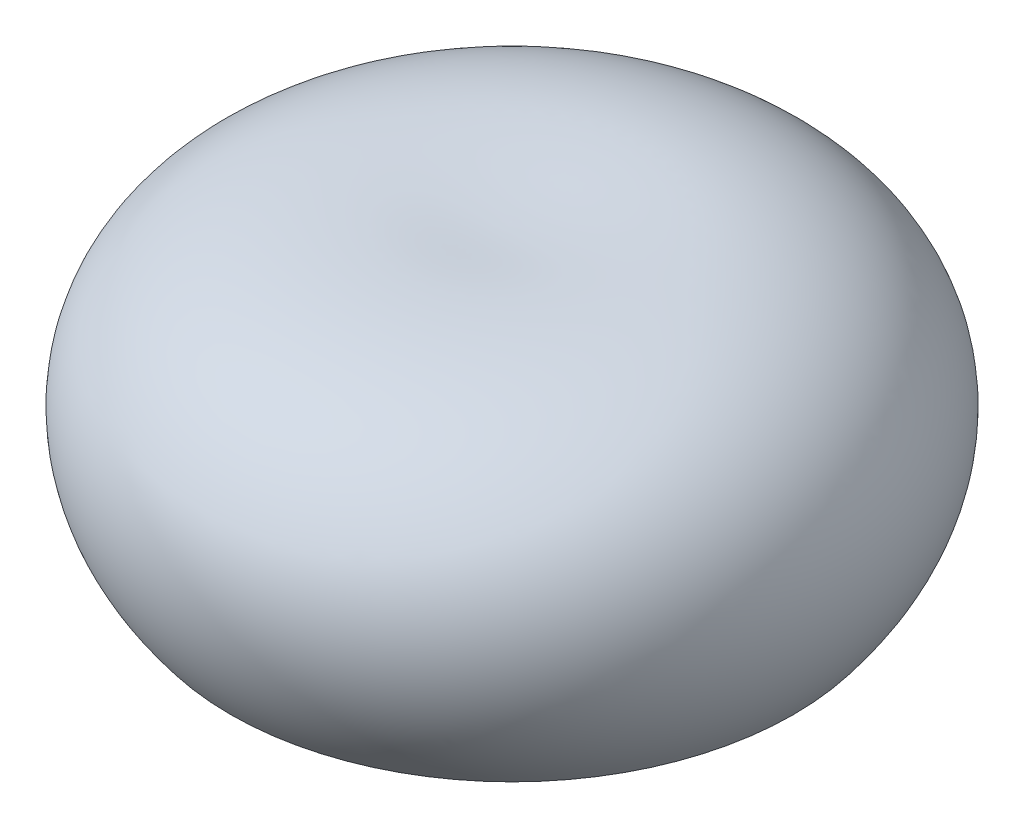
SolidWorks part; units mm, degrees
ref_plane "前视基准面" through (0, 0, 0) normal (0, 0, 1) x (1, 0, 0)
ref_plane "上视基准面" through (0, 0, 0) normal (0, 1, 0) x (1, 0, 0)
ref_plane "右视基准面" through (0, 0, 0) normal (1, 0, 0) x (0, 0, -1)
curve "曲线1"
  spline degree 3 poles (0, 7, 0) (0.0738, 6.9995, 0) (0.1783, 6.9989, 0) (0.3064, 7.0015, 0) (0.3805, 7.0034, 0) (0.4416, 7.0054, 0) (0.4951, 7.0074, 0) (0.5433, 7.0093, 0) (0.5877, 7.0113, 0) (0.629, 7.0132, 0) (0.6679, 7.0151, 0) (0.7047, 7.017, 0) (0.7397, 7.0189, 0) (0.7733, 7.0208, 0) (0.8056, 7.0227, 0) (0.8367, 7.0245, 0) (0.8668, 7.0264, 0) (0.8959, 7.0282, 0) (0.9242, 7.03, 0) (0.9518, 7.0318, 0) (0.9786, 7.0335, 0) (1.0048, 7.0353, 0) (1.0305, 7.037, 0) (1.0555, 7.0387, 0) (1.0801, 7.0405, 0) (1.1041, 7.0421, 0) (1.1278, 7.0438, 0) (1.151, 7.0455, 0) (1.1738, 7.0471, 0) (1.1962, 7.0487, 0) (1.2183, 7.0503, 0) (1.2401, 7.0519, 0) (1.2615, 7.0535, 0) (1.2826, 7.055, 0) (1.3035, 7.0566, 0) (1.3241, 7.0581, 0) (1.3444, 7.0596, 0) (1.3645, 7.0611, 0) (1.3843, 7.0626, 0) (1.4039, 7.064, 0) (1.4233, 7.0654, 0) (1.4425, 7.0669, 0) (1.4614, 7.0683, 0) (1.4802, 7.0697, 0) (1.4988, 7.071, 0) (1.5172, 7.0724, 0) (1.5355, 7.0737, 0) (1.5535, 7.0751, 0) (1.5714, 7.0764, 0) (1.5892, 7.0777, 0) (1.6068, 7.0789, 0) (1.6243, 7.0802, 0) (1.6416, 7.0815, 0) (1.6588, 7.0827, 0) (1.6758, 7.0839, 0) (1.6927, 7.0851, 0) (1.7095, 7.0863, 0) (1.7262, 7.0875, 0) (1.7427, 7.0886, 0) (1.7592, 7.0897, 0) (1.7755, 7.0909, 0) (1.7917, 7.092, 0) (1.8078, 7.0931, 0) (1.8238, 7.0941, 0) (1.8397, 7.0952, 0) (1.8555, 7.0962, 0) (1.8713, 7.0973, 0) (1.8869, 7.0983, 0) (1.9024, 7.0993, 0) (1.9178, 7.1003, 0) (1.9332, 7.1012, 0) (1.9485, 7.1022, 0) (1.9636, 7.1031, 0) (1.9788, 7.104, 0) (1.9938, 7.1049, 0) (2.0087, 7.1058, 0) (2.0236, 7.1067, 0) (2.0384, 7.1076, 0) (2.0531, 7.1084, 0) (2.0678, 7.1092, 0) (2.0823, 7.1101, 0) (2.0969, 7.1109, 0) (2.1113, 7.1116, 0) (2.1257, 7.1124, 0) (2.14, 7.1132, 0) (2.1543, 7.1139, 0) (2.1684, 7.1147, 0) (2.1826, 7.1154, 0) (2.1966, 7.1161, 0) (2.2107, 7.1167, 0) (2.2246, 7.1174, 0) (2.2385, 7.1181, 0) (2.2524, 7.1187, 0) (2.2661, 7.1193, 0) (2.2799, 7.1199, 0) (2.2936, 7.1205, 0) (2.3072, 7.1211, 0) (2.3208, 7.1217, 0) (2.3343, 7.1222, 0) (2.3478, 7.1228, 0) (2.3612, 7.1233, 0) (2.3746, 7.1238, 0) (2.3879, 7.1243, 0) (2.4012, 7.1248, 0) (2.4145, 7.1253, 0) (2.4277, 7.1257, 0) (2.4408, 7.1262, 0) (2.4539, 7.1266, 0) (2.467, 7.127, 0) (2.48, 7.1274, 0) (2.493, 7.1278, 0) (2.506, 7.1281, 0) (2.5189, 7.1285, 0) (2.5317, 7.1288, 0) (2.5446, 7.1292, 0) (2.5574, 7.1295, 0) (2.5701, 7.1298, 0) (2.5828, 7.1301, 0) (2.5955, 7.1303, 0) (2.6081, 7.1306, 0) (2.6207, 7.1308, 0) (2.6333, 7.1311, 0) (2.6458, 7.1313, 0) (2.6583, 7.1315, 0) (2.6708, 7.1317, 0) (2.6832, 7.1318, 0) (2.6956, 7.132, 0) (2.708, 7.1321, 0) (2.7203, 7.1323, 0) (2.7326, 7.1324, 0) (2.7449, 7.1325, 0) (2.7571, 7.1326, 0) (2.7693, 7.1327, 0) (2.7815, 7.1327, 0) (2.7937, 7.1328, 0) (2.8058, 7.1328, 0) (2.8179, 7.1328, 0) (2.8299, 7.1329, 0) (2.8419, 7.1328, 0) (2.8539, 7.1328, 0) (2.8659, 7.1328, 0) (2.8779, 7.1328, 0) (2.8898, 7.1327, 0) (2.9017, 7.1326, 0) (2.9135, 7.1325, 0) (2.9254, 7.1324, 0) (2.9372, 7.1323, 0) (2.949, 7.1322, 0) (2.9607, 7.1321, 0) (2.9725, 7.1319, 0) (2.9842, 7.1317, 0) (2.9958, 7.1316, 0) (3.0075, 7.1314, 0) (3.0191, 7.1312, 0) (3.0307, 7.1309, 0) (3.0423, 7.1307, 0) (3.0539, 7.1305, 0) (3.0654, 7.1302, 0) (3.0769, 7.1299, 0) (3.0884, 7.1296, 0) (3.0999, 7.1293, 0) (3.1114, 7.129, 0) (3.1228, 7.1287, 0) (3.1342, 7.1284, 0) (3.1456, 7.128, 0) (3.1569, 7.1277, 0) (3.1683, 7.1273, 0) (3.1796, 7.1269, 0) (3.1909, 7.1265, 0) (3.2021, 7.1261, 0) (3.2134, 7.1256, 0) (3.2246, 7.1252, 0) (3.2358, 7.1247, 0) (3.247, 7.1243, 0) (3.2582, 7.1238, 0) (3.2694, 7.1233, 0) (3.2805, 7.1228, 0) (3.2916, 7.1222, 0) (3.3027, 7.1217, 0) (3.3138, 7.1211, 0) (3.3248, 7.1206, 0) (3.3359, 7.12, 0) (3.3469, 7.1194, 0) (3.3579, 7.1188, 0) (3.3689, 7.1182, 0) (3.3798, 7.1176, 0) (3.3908, 7.1169, 0) (3.4017, 7.1163, 0) (3.4126, 7.1156, 0) (3.4235, 7.1149, 0) (3.4344, 7.1142, 0) (3.4452, 7.1135, 0) (3.4561, 7.1128, 0) (3.4669, 7.1121, 0) (3.4777, 7.1113, 0) (3.4885, 7.1106, 0) (3.4993, 7.1098, 0) (3.51, 7.109, 0) (3.5208, 7.1082, 0) (3.5315, 7.1074, 0) (3.5422, 7.1066, 0) (3.5529, 7.1058, 0) (3.5635, 7.1049, 0) (3.5742, 7.104, 0) (3.5848, 7.1032, 0) (3.5955, 7.1023, 0) (3.6061, 7.1014, 0) (3.6167, 7.1005, 0) (3.6273, 7.0995, 0) (3.6378, 7.0986, 0) (3.6484, 7.0977, 0) (3.6589, 7.0967, 0) (3.6694, 7.0957, 0) (3.6799, 7.0947, 0) (3.6904, 7.0937, 0) (3.7009, 7.0927, 0) (3.7114, 7.0917, 0) (3.7218, 7.0906, 0) (3.7322, 7.0896, 0) (3.7426, 7.0885, 0) (3.753, 7.0874, 0) (3.7634, 7.0863, 0) (3.7738, 7.0852, 0) (3.7842, 7.0841, 0) (3.7945, 7.083, 0) (3.8049, 7.0818, 0) (3.8152, 7.0807, 0) (3.8255, 7.0795, 0) (3.8358, 7.0783, 0) (3.846, 7.0771, 0) (3.8563, 7.0759, 0) (3.8666, 7.0747, 0) (3.8768, 7.0734, 0) (3.887, 7.0722, 0) (3.8972, 7.0709, 0) (3.9074, 7.0697, 0) (3.9176, 7.0684, 0) (3.9278, 7.0671, 0) (3.938, 7.0658, 0) (3.9481, 7.0644, 0) (3.9582, 7.0631, 0) (3.9684, 7.0618, 0) (3.9785, 7.0604, 0) (3.9886, 7.059, 0) (3.9986, 7.0576, 0) (4.0087, 7.0562, 0) (4.0188, 7.0548, 0) (4.0288, 7.0534, 0) (4.0389, 7.0519, 0) (4.0489, 7.0505, 0) (4.0589, 7.049, 0) (4.0689, 7.0475, 0) (4.0789, 7.0461, 0) (4.0889, 7.0445, 0) (4.0988, 7.043, 0) (4.1088, 7.0415, 0) (4.1187, 7.04, 0) (4.1286, 7.0384, 0) (4.1386, 7.0368, 0) (4.1485, 7.0352, 0) (4.1584, 7.0337, 0) (4.1682, 7.032, 0) (4.1781, 7.0304, 0) (4.188, 7.0288, 0) (4.1978, 7.0271, 0) (4.2076, 7.0255, 0) (4.2175, 7.0238, 0) (4.2273, 7.0221, 0) (4.2371, 7.0204, 0) (4.2469, 7.0187, 0) (4.2567, 7.017, 0) (4.2664, 7.0153, 0) (4.2762, 7.0135, 0) (4.2859, 7.0118, 0) (4.2957, 7.01, 0) (4.3054, 7.0082, 0) (4.3151, 7.0064, 0) (4.3248, 7.0046, 0) (4.3345, 7.0028, 0) (4.3442, 7.0009, 0) (4.3539, 6.9991, 0) (4.3635, 6.9972, 0) (4.3732, 6.9953, 0) (4.3828, 6.9934, 0) (4.3924, 6.9915, 0) (4.4021, 6.9896, 0) (4.4117, 6.9877, 0) (4.4213, 6.9858, 0) (4.4309, 6.9838, 0) (4.4404, 6.9818, 0) (4.45, 6.9799, 0) (4.4596, 6.9779, 0) (4.4691, 6.9759, 0) (4.4786, 6.9738, 0) (4.4882, 6.9718, 0) (4.4977, 6.9698, 0) (4.5072, 6.9677, 0) (4.5167, 6.9656, 0) (4.5262, 6.9635, 0) (4.5356, 6.9615, 0) (4.5451, 6.9593, 0) (4.5546, 6.9572, 0) (4.564, 6.9551, 0) (4.5734, 6.9529, 0) (4.5829, 6.9508, 0) (4.5923, 6.9486, 0) (4.6017, 6.9464, 0) (4.6111, 6.9442, 0) (4.6205, 6.942, 0) (4.6299, 6.9398, 0) (4.6392, 6.9375, 0) (4.6486, 6.9353, 0) (4.6579, 6.933, 0) (4.6673, 6.9307, 0) (4.6766, 6.9284, 0) (4.6859, 6.9261, 0) (4.6952, 6.9238, 0) (4.7045, 6.9215, 0) (4.7138, 6.9192, 0) (4.7231, 6.9168, 0) (4.7324, 6.9144, 0) (4.7416, 6.912, 0) (4.7509, 6.9096, 0) (4.7601, 6.9072, 0) (4.7693, 6.9048, 0) (4.7786, 6.9024, 0) (4.7878, 6.8999, 0) (4.797, 6.8975, 0) (4.8062, 6.895, 0) (4.8154, 6.8925, 0) (4.8245, 6.89, 0) (4.8337, 6.8875, 0) (4.8429, 6.885, 0) (4.852, 6.8824, 0) (4.8612, 6.8799, 0) (4.8703, 6.8773, 0) (4.8794, 6.8747, 0) (4.8885, 6.8721, 0) (4.8976, 6.8695, 0) (4.9067, 6.8669, 0) (4.9158, 6.8643, 0) (4.9249, 6.8616, 0) (4.9339, 6.859, 0) (4.943, 6.8563, 0) (4.952, 6.8536, 0) (4.9611, 6.8509, 0) (4.9701, 6.8482, 0) (4.9791, 6.8455, 0) (4.9881, 6.8428, 0) (4.9971, 6.84, 0) (5.0061, 6.8372, 0) (5.0151, 6.8345, 0) (5.0241, 6.8317, 0) (5.0331, 6.8289, 0) (5.042, 6.8261, 0) (5.051, 6.8232, 0) (5.0599, 6.8204, 0) (5.0688, 6.8175, 0) (5.0778, 6.8147, 0) (5.0867, 6.8118, 0) (5.0956, 6.8089, 0) (5.1045, 6.806, 0) (5.1134, 6.803, 0) (5.1222, 6.8001, 0) (5.1311, 6.7971, 0) (5.14, 6.7942, 0) (5.1488, 6.7912, 0) (5.1576, 6.7882, 0) (5.1665, 6.7852, 0) (5.1753, 6.7822, 0) (5.1841, 6.7792, 0) (5.1929, 6.7761, 0) (5.2017, 6.7731, 0) (5.2105, 6.77, 0) (5.2193, 6.7669, 0) (5.228, 6.7638, 0) (5.2368, 6.7607, 0) (5.2456, 6.7576, 0) (5.2543, 6.7544, 0) (5.263, 6.7513, 0) (5.2718, 6.7481, 0) (5.2805, 6.7449, 0) (5.2892, 6.7417, 0) (5.2979, 6.7385, 0) (5.3066, 6.7353, 0) (5.3153, 6.7321, 0) (5.3239, 6.7288, 0) (5.3326, 6.7256, 0) (5.3412, 6.7223, 0) (5.3499, 6.719, 0) (5.3585, 6.7157, 0) (5.3671, 6.7124, 0) (5.3758, 6.709, 0) (5.3844, 6.7057, 0) (5.393, 6.7023, 0) (5.4016, 6.699, 0) (5.4102, 6.6956, 0) (5.4187, 6.6922, 0) (5.4273, 6.6888, 0) (5.4359, 6.6854, 0) (5.4444, 6.6819, 0) (5.4529, 6.6785, 0) (5.4615, 6.675, 0) (5.47, 6.6715, 0) (5.4785, 6.668, 0) (5.487, 6.6645, 0) (5.4955, 6.661, 0) (5.504, 6.6575, 0) (5.5125, 6.6539, 0) (5.5209, 6.6503, 0) (5.5294, 6.6468, 0) (5.5378, 6.6432, 0) (5.5463, 6.6396, 0) (5.5547, 6.6359, 0) (5.5631, 6.6323, 0) (5.5716, 6.6287, 0) (5.58, 6.625, 0) (5.5884, 6.6213, 0) (5.5968, 6.6176, 0) (5.6051, 6.6139, 0) (5.6135, 6.6102, 0) (5.6219, 6.6065, 0) (5.6302, 6.6027, 0) (5.6386, 6.599, 0) (5.6469, 6.5952, 0) (5.6552, 6.5914, 0) (5.6635, 6.5876, 0) (5.6719, 6.5838, 0) (5.6802, 6.58, 0) (5.6884, 6.5761, 0) (5.6967, 6.5723, 0) (5.705, 6.5684, 0) (5.7133, 6.5645, 0) (5.7215, 6.5606, 0) (5.7298, 6.5567, 0) (5.738, 6.5528, 0) (5.7462, 6.5488, 0) (5.7544, 6.5449, 0) (5.7627, 6.5409, 0) (5.7709, 6.5369, 0) (5.7791, 6.5329, 0) (5.7872, 6.5289, 0) (5.7954, 6.5249, 0) (5.8036, 6.5208, 0) (5.8117, 6.5168, 0) (5.8199, 6.5127, 0) (5.828, 6.5086, 0) (5.8361, 6.5045, 0) (5.8443, 6.5004, 0) (5.8524, 6.4962, 0) (5.8605, 6.4921, 0) (5.8686, 6.4879, 0) (5.8766, 6.4838, 0) (5.8847, 6.4796, 0) (5.8928, 6.4754, 0) (5.9008, 6.4712, 0) (5.9089, 6.4669, 0) (5.9169, 6.4627, 0) (5.9249, 6.4584, 0) (5.933, 6.4541, 0) (5.941, 6.4499, 0) (5.949, 6.4456, 0) (5.957, 6.4412, 0) (5.9649, 6.4369, 0) (5.9729, 6.4326, 0) (5.9809, 6.4282, 0) (5.9888, 6.4238, 0) (5.9968, 6.4194, 0) (6.0047, 6.415, 0) (6.0126, 6.4106, 0) (6.0206, 6.4062, 0) (6.0285, 6.4017, 0) (6.0364, 6.3972, 0) (6.0442, 6.3928, 0) (6.0521, 6.3883, 0) (6.06, 6.3838, 0) (6.0679, 6.3792, 0) (6.0757, 6.3747, 0) (6.0835, 6.3701, 0) (6.0914, 6.3656, 0) (6.0992, 6.361, 0) (6.107, 6.3564, 0) (6.1148, 6.3518, 0) (6.1226, 6.3471, 0) (6.1304, 6.3425, 0) (6.1382, 6.3378, 0) (6.1459, 6.3332, 0) (6.1537, 6.3285, 0) (6.1614, 6.3238, 0) (6.1692, 6.319, 0) (6.1769, 6.3143, 0) (6.1846, 6.3096, 0) (6.1923, 6.3048, 0) (6.2, 6.3, 0) (6.2077, 6.2952, 0) (6.2154, 6.2904, 0) (6.223, 6.2856, 0) (6.2307, 6.2807, 0) (6.2383, 6.2759, 0) (6.246, 6.271, 0) (6.2536, 6.2661, 0) (6.2612, 6.2612, 0) (6.2688, 6.2563, 0) (6.2764, 6.2514, 0) (6.284, 6.2464, 0) (6.2916, 6.2415, 0) (6.2991, 6.2365, 0) (6.3067, 6.2315, 0) (6.3143, 6.2265, 0) (6.3218, 6.2214, 0) (6.3293, 6.2164, 0) (6.3368, 6.2113, 0) (6.3443, 6.2063, 0) (6.3518, 6.2012, 0) (6.3593, 6.1961, 0) (6.3668, 6.191, 0) (6.3743, 6.1858, 0) (6.3817, 6.1807, 0) (6.3892, 6.1755, 0) (6.3966, 6.1703, 0) (6.404, 6.1651, 0) (6.4114, 6.1599, 0) (6.4189, 6.1547, 0) (6.4262, 6.1494, 0) (6.4336, 6.1442, 0) (6.441, 6.1389, 0) (6.4484, 6.1336, 0) (6.4557, 6.1283, 0) (6.4631, 6.123, 0) (6.4704, 6.1177, 0) (6.4777, 6.1123, 0) (6.485, 6.1069, 0) (6.4923, 6.1015, 0) (6.4996, 6.0961, 0) (6.5069, 6.0907, 0) (6.5142, 6.0853, 0) (6.5214, 6.0798, 0) (6.5287, 6.0744, 0) (6.5359, 6.0689, 0) (6.5431, 6.0634, 0) (6.5503, 6.0579, 0) (6.5575, 6.0523, 0) (6.5647, 6.0468, 0) (6.5719, 6.0412, 0) (6.5791, 6.0356, 0) (6.5862, 6.0301, 0) (6.5934, 6.0244, 0) (6.6005, 6.0188, 0) (6.6077, 6.0132, 0) (6.6148, 6.0075, 0) (6.6219, 6.0018, 0) (6.629, 5.9961, 0) (6.6361, 5.9904, 0) (6.6431, 5.9847, 0) (6.6502, 5.979, 0) (6.6572, 5.9732, 0) (6.6643, 5.9674, 0) (6.6713, 5.9616, 0) (6.6783, 5.9558, 0) (6.6853, 5.95, 0) (6.6923, 5.9441, 0) (6.6993, 5.9383, 0) (6.7063, 5.9324, 0) (6.7132, 5.9265, 0) (6.7202, 5.9206, 0) (6.7271, 5.9147, 0) (6.734, 5.9087, 0) (6.7409, 5.9028, 0) (6.7478, 5.8968, 0) (6.7547, 5.8908, 0) (6.7616, 5.8848, 0) (6.7685, 5.8788, 0) (6.7753, 5.8727, 0) (6.7822, 5.8667, 0) (6.789, 5.8606, 0) (6.7958, 5.8545, 0) (6.8026, 5.8484, 0) (6.8094, 5.8423, 0) (6.8162, 5.8361, 0) (6.823, 5.83, 0) (6.8297, 5.8238, 0) (6.8365, 5.8176, 0) (6.8432, 5.8114, 0) (6.8499, 5.8051, 0) (6.8566, 5.7989, 0) (6.8633, 5.7926, 0) (6.87, 5.7863, 0) (6.8767, 5.78, 0) (6.8834, 5.7737, 0) (6.89, 5.7674, 0) (6.8966, 5.761, 0) (6.9033, 5.7547, 0) (6.9099, 5.7483, 0) (6.9165, 5.7419, 0) (6.9231, 5.7355, 0) (6.9296, 5.729, 0) (6.9362, 5.7226, 0) (6.9428, 5.7161, 0) (6.9493, 5.7096, 0) (6.9558, 5.7031, 0) (6.9623, 5.6966, 0) (6.9688, 5.69, 0) (6.9753, 5.6835, 0) (6.9818, 5.6769, 0) (6.9882, 5.6703, 0) (6.9947, 5.6637, 0) (7.0011, 5.657, 0) (7.0075, 5.6504, 0) (7.014, 5.6437, 0) (7.0204, 5.637, 0) (7.0267, 5.6303, 0) (7.0331, 5.6236, 0) (7.0395, 5.6169, 0) (7.0458, 5.6101, 0) (7.0521, 5.6033, 0) (7.0584, 5.5965, 0) (7.0647, 5.5897, 0) (7.071, 5.5829, 0) (7.0773, 5.576, 0) (7.0836, 5.5692, 0) (7.0898, 5.5623, 0) (7.0961, 5.5554, 0) (7.1023, 5.5484, 0) (7.1085, 5.5415, 0) (7.1147, 5.5345, 0) (7.1209, 5.5276, 0) (7.127, 5.5206, 0) (7.1332, 5.5135, 0) (7.1393, 5.5065, 0) (7.1454, 5.4995, 0) (7.1515, 5.4924, 0) (7.1576, 5.4853, 0) (7.1637, 5.4782, 0) (7.1698, 5.4711, 0) (7.1758, 5.4639, 0) (7.1819, 5.4567, 0) (7.1879, 5.4496, 0) (7.1939, 5.4424, 0) (7.1999, 5.4351, 0) (7.2059, 5.4279, 0) (7.2119, 5.4206, 0) (7.2178, 5.4134, 0) (7.2238, 5.4061, 0) (7.2297, 5.3987, 0) (7.2356, 5.3914, 0) (7.2415, 5.3841, 0) (7.2474, 5.3767, 0) (7.2532, 5.3693, 0) (7.2591, 5.3619, 0) (7.2649, 5.3544, 0) (7.2707, 5.347, 0) (7.2765, 5.3395, 0) (7.2823, 5.332, 0) (7.2881, 5.3245, 0) (7.2939, 5.317, 0) (7.2996, 5.3094, 0) (7.3053, 5.3019, 0) (7.311, 5.2943, 0) (7.3167, 5.2867, 0) (7.3224, 5.279, 0) (7.3281, 5.2714, 0) (7.3337, 5.2637, 0) (7.3394, 5.256, 0) (7.345, 5.2483, 0) (7.3506, 5.2406, 0) (7.3562, 5.2329, 0) (7.3618, 5.2251, 0) (7.3673, 5.2173, 0) (7.3729, 5.2095, 0) (7.3784, 5.2017, 0) (7.3839, 5.1938, 0) (7.3894, 5.1859, 0) (7.3949, 5.1781, 0) (7.4003, 5.1702, 0) (7.4058, 5.1622, 0) (7.4112, 5.1543, 0) (7.4166, 5.1463, 0) (7.422, 5.1383, 0) (7.4274, 5.1303, 0) (7.4327, 5.1223, 0) (7.4381, 5.1142, 0) (7.4434, 5.1061, 0) (7.4487, 5.098, 0) (7.454, 5.0899, 0) (7.4593, 5.0818, 0) (7.4646, 5.0736, 0) (7.4698, 5.0655, 0) (7.475, 5.0573, 0) (7.4802, 5.049, 0) (7.4854, 5.0408, 0) (7.4906, 5.0325, 0) (7.4958, 5.0243, 0) (7.5009, 5.016, 0) (7.506, 5.0076, 0) (7.5111, 4.9993, 0) (7.5162, 4.9909, 0) (7.5213, 4.9825, 0) (7.5263, 4.9741, 0) (7.5314, 4.9657, 0) (7.5364, 4.9572, 0) (7.5414, 4.9487, 0) (7.5464, 4.9402, 0) (7.5513, 4.9317, 0) (7.5563, 4.9232, 0) (7.5612, 4.9146, 0) (7.5661, 4.906, 0) (7.571, 4.8974, 0) (7.5758, 4.8888, 0) (7.5807, 4.8801, 0) (7.5855, 4.8715, 0) (7.5903, 4.8628, 0) (7.5951, 4.8541, 0) (7.5999, 4.8453, 0) (7.6047, 4.8366, 0) (7.6094, 4.8278, 0) (7.6141, 4.819, 0) (7.6188, 4.8101, 0) (7.6235, 4.8013, 0) (7.6282, 4.7924, 0) (7.6328, 4.7835, 0) (7.6374, 4.7746, 0) (7.642, 4.7656, 0) (7.6466, 4.7567, 0) (7.6512, 4.7477, 0) (7.6557, 4.7387, 0) (7.6602, 4.7296, 0) (7.6647, 4.7206, 0) (7.6692, 4.7115, 0) (7.6737, 4.7024, 0) (7.6781, 4.6932, 0) (7.6825, 4.6841, 0) (7.6869, 4.6749, 0) (7.6913, 4.6657, 0) (7.6957, 4.6565, 0) (7.7, 4.6472, 0) (7.7043, 4.638, 0) (7.7086, 4.6287, 0) (7.7129, 4.6193, 0) (7.7172, 4.61, 0) (7.7214, 4.6006, 0) (7.7256, 4.5912, 0) (7.7298, 4.5818, 0) (7.734, 4.5724, 0) (7.7381, 4.5629, 0) (7.7422, 4.5534, 0) (7.7463, 4.5439, 0) (7.7504, 4.5344, 0) (7.7545, 4.5248, 0) (7.7585, 4.5152, 0) (7.7625, 4.5056, 0) (7.7665, 4.496, 0) (7.7705, 4.4863, 0) (7.7744, 4.4766, 0) (7.7784, 4.4669, 0) (7.7823, 4.4571, 0) (7.7861, 4.4474, 0) (7.79, 4.4376, 0) (7.7938, 4.4278, 0) (7.7976, 4.4179, 0) (7.8014, 4.4081, 0) (7.8052, 4.3982, 0) (7.8089, 4.3882, 0) (7.8127, 4.3783, 0) (7.8164, 4.3683, 0) (7.82, 4.3583, 0) (7.8237, 4.3483, 0) (7.8273, 4.3382, 0) (7.8309, 4.3282, 0) (7.8345, 4.3181, 0) (7.838, 4.3079, 0) (7.8415, 4.2978, 0) (7.845, 4.2876, 0) (7.8485, 4.2774, 0) (7.852, 4.2671, 0) (7.8554, 4.2569, 0) (7.8588, 4.2466, 0) (7.8622, 4.2362, 0) (7.8655, 4.2259, 0) (7.8688, 4.2155, 0) (7.8721, 4.2051, 0) (7.8754, 4.1947, 0) (7.8786, 4.1842, 0) (7.8819, 4.1737, 0) (7.8851, 4.1632, 0) (7.8882, 4.1527, 0) (7.8914, 4.1421, 0) (7.8945, 4.1315, 0) (7.8976, 4.1209, 0) (7.9006, 4.1102, 0) (7.9037, 4.0995, 0) (7.9067, 4.0888, 0) (7.9096, 4.078, 0) (7.9126, 4.0673, 0) (7.9155, 4.0565, 0) (7.9184, 4.0456, 0) (7.9213, 4.0348, 0) (7.9241, 4.0239, 0) (7.9269, 4.0129, 0) (7.9297, 4.002, 0) (7.9325, 3.991, 0) (7.9352, 3.98, 0) (7.9379, 3.9689, 0) (7.9406, 3.9579, 0) (7.9432, 3.9468, 0) (7.9458, 3.9356, 0) (7.9484, 3.9244, 0) (7.951, 3.9132, 0) (7.9535, 3.902, 0) (7.956, 3.8908, 0) (7.9584, 3.8795, 0) (7.9609, 3.8681, 0) (7.9633, 3.8568, 0) (7.9656, 3.8454, 0) (7.968, 3.834, 0) (7.9703, 3.8225, 0) (7.9725, 3.811, 0) (7.9748, 3.7995, 0) (7.977, 3.7879, 0) (7.9792, 3.7763, 0) (7.9813, 3.7647, 0) (7.9834, 3.7531, 0) (7.9855, 3.7414, 0) (7.9876, 3.7297, 0) (7.9896, 3.7179, 0) (7.9916, 3.7061, 0) (7.9935, 3.6943, 0) (7.9955, 3.6824, 0) (7.9973, 3.6705, 0) (7.9992, 3.6586, 0) (8.001, 3.6466, 0) (8.0028, 3.6346, 0) (8.0045, 3.6226, 0) (8.0062, 3.6105, 0) (8.0079, 3.5984, 0) (8.0096, 3.5863, 0) (8.0112, 3.5741, 0) (8.0127, 3.5619, 0) (8.0143, 3.5496, 0) (8.0158, 3.5373, 0) (8.0172, 3.525, 0) (8.0187, 3.5126, 0) (8.0201, 3.5002, 0) (8.0214, 3.4878, 0) (8.0227, 3.4753, 0) (8.024, 3.4628, 0) (8.0252, 3.4502, 0) (8.0264, 3.4376, 0) (8.0276, 3.425, 0) (8.0287, 3.4123, 0) (8.0298, 3.3996, 0) (8.0308, 3.3868, 0) (8.0318, 3.374, 0) (8.0328, 3.3612, 0) (8.0337, 3.3483, 0) (8.0346, 3.3354, 0) (8.0354, 3.3224, 0) (8.0362, 3.3094, 0) (8.037, 3.2964, 0) (8.0377, 3.2833, 0) (8.0384, 3.2701, 0) (8.039, 3.257, 0) (8.0396, 3.2437, 0) (8.0401, 3.2305, 0) (8.0406, 3.2172, 0) (8.0411, 3.2038, 0) (8.0415, 3.1904, 0) (8.0419, 3.177, 0) (8.0422, 3.1635, 0) (8.0425, 3.1499, 0) (8.0427, 3.1364, 0) (8.0429, 3.1227, 0) (8.043, 3.109, 0) (8.0431, 3.0953, 0) (8.0431, 3.0815, 0) (8.0431, 3.0677, 0) (8.0431, 3.0539, 0) (8.043, 3.0399, 0) (8.0428, 3.026, 0) (8.0426, 3.0119, 0) (8.0423, 2.9979, 0) (8.042, 2.9837, 0) (8.0417, 2.9696, 0) (8.0413, 2.9553, 0) (8.0408, 2.9411, 0) (8.0403, 2.9267, 0) (8.0397, 2.9123, 0) (8.0391, 2.8979, 0) (8.0384, 2.8834, 0) (8.0377, 2.8688, 0) (8.0369, 2.8542, 0) (8.0361, 2.8396, 0) (8.0352, 2.8248, 0) (8.0342, 2.8101, 0) (8.0332, 2.7952, 0) (8.0321, 2.7803, 0) (8.031, 2.7653, 0) (8.0298, 2.7503, 0) (8.0286, 2.7352, 0) (8.0272, 2.7201, 0) (8.0259, 2.7049, 0) (8.0244, 2.6896, 0) (8.0229, 2.6743, 0) (8.0214, 2.6589, 0) (8.0197, 2.6434, 0) (8.018, 2.6279, 0) (8.0163, 2.6123, 0) (8.0144, 2.5966, 0) (8.0125, 2.5809, 0) (8.0106, 2.5651, 0) (8.0085, 2.5492, 0) (8.0064, 2.5332, 0) (8.0042, 2.5172, 0) (8.002, 2.5011, 0) (7.9997, 2.4849, 0) (7.9973, 2.4687, 0) (7.9948, 2.4523, 0) (7.9922, 2.4359, 0) (7.9896, 2.4194, 0) (7.9869, 2.4028, 0) (7.9841, 2.3862, 0) (7.9812, 2.3694, 0) (7.9783, 2.3526, 0) (7.9752, 2.3357, 0) (7.9721, 2.3187, 0) (7.9689, 2.3016, 0) (7.9656, 2.2844, 0) (7.9622, 2.2672, 0) (7.9587, 2.2498, 0) (7.9552, 2.2324, 0) (7.9515, 2.2148, 0) (7.9477, 2.1971, 0) (7.9439, 2.1794, 0) (7.9399, 2.1615, 0) (7.9359, 2.1435, 0) (7.9317, 2.1255, 0) (7.9274, 2.1073, 0) (7.9231, 2.089, 0) (7.9186, 2.0706, 0) (7.914, 2.052, 0) (7.9093, 2.0334, 0) (7.9045, 2.0146, 0) (7.8995, 1.9957, 0) (7.8945, 1.9767, 0) (7.8893, 1.9576, 0) (7.884, 1.9383, 0) (7.8786, 1.9189, 0) (7.873, 1.8993, 0) (7.8673, 1.8796, 0) (7.8615, 1.8597, 0) (7.8555, 1.8397, 0) (7.8494, 1.8196, 0) (7.8431, 1.7993, 0) (7.8367, 1.7788, 0) (7.8301, 1.7581, 0) (7.8234, 1.7373, 0) (7.8165, 1.7163, 0) (7.8094, 1.6951, 0) (7.8022, 1.6738, 0) (7.7948, 1.6522, 0) (7.7872, 1.6304, 0) (7.7794, 1.6084, 0) (7.7714, 1.5862, 0) (7.7632, 1.5638, 0) (7.7548, 1.5411, 0) (7.7461, 1.5182, 0) (7.7373, 1.4951, 0) (7.7282, 1.4717, 0) (7.7188, 1.448, 0) (7.7093, 1.424, 0) (7.6994, 1.3998, 0) (7.6893, 1.3752, 0) (7.6789, 1.3503, 0) (7.6681, 1.3251, 0) (7.6571, 1.2995, 0) (7.6457, 1.2735, 0) (7.634, 1.2471, 0) (7.6219, 1.2203, 0) (7.6095, 1.1931, 0) (7.5966, 1.1654, 0) (7.5833, 1.1372, 0) (7.5695, 1.1084, 0) (7.5552, 1.0791, 0) (7.5404, 1.0491, 0) (7.525, 1.0185, 0) (7.5091, 0.9872, 0) (7.4924, 0.9551, 0) (7.475, 0.9221, 0) (7.4568, 0.8881, 0) (7.4377, 0.8532, 0) (7.4177, 0.817, 0) (7.3965, 0.7795, 0) (7.374, 0.7405, 0) (7.3502, 0.6997, 0) (7.3246, 0.6569, 0) (7.297, 0.6116, 0) (7.2669, 0.5632, 0) (7.2337, 0.511, 0) (7.1963, 0.4536, 0) (7.1528, 0.3886, 0) (7.0992, 0.3106, 0) (7.0057, 0.179, 0) (6.9269, 0.0739, 0) (6.8715, 0, 0) knots 0 0 0 0 0.016298 0.023067 0.028274 0.032675 0.036563 0.040086 0.043333 0.046364 0.049217 0.051922 0.054501 0.056971 0.059346 0.061636 0.063851 0.065998 0.068084 0.070114 0.072093 0.074025 0.075913 0.077761 0.079571 0.081346 0.083088 0.0848 0.086482 0.088137 0.089766 0.091371 0.092952 0.094511 0.096049 0.097567 0.099066 0.100547 0.10201 0.103456 0.104887 0.106302 0.107702 0.109087 0.110459 0.111818 0.113164 0.114497 0.115819 0.117129 0.118427 0.119715 0.120993 0.12226 0.123518 0.124766 0.126004 0.127234 0.128455 0.129667 0.130871 0.132067 0.133256 0.134436 0.135609 0.136775 0.137933 0.139085 0.14023 0.141368 0.1425 0.143626 0.144745 0.145859 0.146966 0.148068 0.149164 0.150255 0.15134 0.15242 0.153495 0.154564 0.155629 0.156689 0.157744 0.158794 0.159839 0.160881 0.161917 0.16295 0.163978 0.165001 0.166021 0.167037 0.168049 0.169056 0.17006 0.17106 0.172057 0.173049 0.174039 0.175024 0.176006 0.176985 0.17796 0.178932 0.179901 0.180866 0.181829 0.182788 0.183744 0.184697 0.185647 0.186594 0.187538 0.18848 0.189418 0.190354 0.191287 0.192217 0.193145 0.19407 0.194992 0.195912 0.19683 0.197744 0.198657 0.199567 0.200474 0.201379 0.202282 0.203183 0.204081 0.204977 0.205871 0.206762 0.207652 0.208539 0.209424 0.210307 0.211188 0.212067 0.212944 0.213819 0.214692 0.215563 0.216432 0.2173 0.218165 0.219028 0.21989 0.22075 0.221608 0.222464 0.223318 0.224171 0.225022 0.225872 0.226719 0.227565 0.228409 0.229252 0.230093 0.230933 0.23177 0.232607 0.233442 0.234275 0.235106 0.235937 0.236765 0.237593 0.238418 0.239243 0.240066 0.240887 0.241707 0.242526 0.243343 0.244159 0.244974 0.245787 0.246599 0.24741 0.248219 0.249027 0.249834 0.25064 0.251444 0.252247 0.253049 0.253849 0.254649 0.255447 0.256244 0.25704 0.257834 0.258628 0.25942 0.260212 0.261002 0.261791 0.262579 0.263366 0.264151 0.264936 0.26572 0.266502 0.267284 0.268064 0.268844 0.269622 0.2704 0.271176 0.271951 0.272726 0.273499 0.274272 0.275043 0.275814 0.276583 0.277352 0.27812 0.278887 0.279653 0.280418 0.281182 0.281945 0.282707 0.283469 0.284229 0.284989 0.285748 0.286506 0.287263 0.28802 0.288775 0.28953 0.290284 0.291037 0.291789 0.29254 0.293291 0.294041 0.29479 0.295538 0.296286 0.297033 0.297779 0.298524 0.299269 0.300012 0.300756 0.301498 0.302239 0.30298 0.303721 0.30446 0.305199 0.305937 0.306674 0.307411 0.308147 0.308882 0.309617 0.310351 0.311085 0.311817 0.312549 0.313281 0.314012 0.314742 0.315471 0.3162 0.316928 0.317656 0.318383 0.31911 0.319835 0.320561 0.321285 0.322009 0.322733 0.323456 0.324178 0.3249 0.325621 0.326341 0.327062 0.327781 0.3285 0.329218 0.329936 0.330653 0.33137 0.332086 0.332802 0.333517 0.334232 0.334946 0.33566 0.336373 0.337086 0.337798 0.338509 0.339221 0.339931 0.340641 0.341351 0.34206 0.342769 0.343477 0.344185 0.344892 0.345599 0.346305 0.347011 0.347717 0.348422 0.349126 0.349831 0.350534 0.351238 0.35194 0.352643 0.353345 0.354046 0.354748 0.355448 0.356149 0.356849 0.357548 0.358247 0.358946 0.359644 0.360342 0.361039 0.361737 0.362433 0.36313 0.363826 0.364521 0.365216 0.365911 0.366606 0.3673 0.367994 0.368687 0.36938 0.370073 0.370765 0.371457 0.372149 0.37284 0.373531 0.374222 0.374912 0.375602 0.376291 0.376981 0.37767 0.378358 0.379047 0.379735 0.380422 0.38111 0.381797 0.382483 0.38317 0.383856 0.384542 0.385228 0.385913 0.386598 0.387283 0.387967 0.388651 0.389335 0.390018 0.390702 0.391385 0.392068 0.39275 0.393432 0.394114 0.394796 0.395477 0.396159 0.396839 0.39752 0.3982 0.398881 0.399561 0.40024 0.40092 0.401599 0.402278 0.402957 0.403635 0.404314 0.404992 0.405669 0.406347 0.407024 0.407702 0.408379 0.409055 0.409732 0.410408 0.411084 0.41176 0.412436 0.413112 0.413787 0.414462 0.415137 0.415812 0.416486 0.417161 0.417835 0.418509 0.419183 0.419856 0.42053 0.421203 0.421876 0.422549 0.423222 0.423895 0.424567 0.42524 0.425912 0.426584 0.427256 0.427928 0.428599 0.429271 0.429942 0.430613 0.431284 0.431955 0.432626 0.433296 0.433967 0.434637 0.435307 0.435977 0.436647 0.437317 0.437987 0.438657 0.439326 0.439996 0.440665 0.441334 0.442003 0.442672 0.443341 0.44401 0.444678 0.445347 0.446015 0.446684 0.447352 0.44802 0.448689 0.449357 0.450025 0.450693 0.45136 0.452028 0.452696 0.453363 0.454031 0.454698 0.455366 0.456033 0.456701 0.457368 0.458035 0.458702 0.459369 0.460036 0.460703 0.46137 0.462037 0.462704 0.463371 0.464038 0.464705 0.465372 0.466038 0.466705 0.467372 0.468038 0.468705 0.469372 0.470038 0.470705 0.471372 0.472038 0.472705 0.473371 0.474038 0.474705 0.475371 0.476038 0.476704 0.477371 0.478038 0.478704 0.479371 0.480038 0.480704 0.481371 0.482038 0.482705 0.483372 0.484038 0.484705 0.485372 0.486039 0.486706 0.487373 0.488041 0.488708 0.489375 0.490042 0.49071 0.491377 0.492044 0.492712 0.49338 0.494047 0.494715 0.495383 0.496051 0.496719 0.497387 0.498055 0.498723 0.499392 0.50006 0.500728 0.501397 0.502066 0.502735 0.503404 0.504073 0.504742 0.505411 0.50608 0.50675 0.507419 0.508089 0.508759 0.509429 0.510099 0.510769 0.51144 0.51211 0.512781 0.513452 0.514123 0.514794 0.515465 0.516136 0.516808 0.51748 0.518152 0.518824 0.519496 0.520168 0.520841 0.521514 0.522187 0.52286 0.523533 0.524207 0.52488 0.525554 0.526228 0.526903 0.527577 0.528252 0.528927 0.529602 0.530277 0.530953 0.531629 0.532305 0.532981 0.533657 0.534334 0.535011 0.535688 0.536366 0.537043 0.537721 0.538399 0.539078 0.539756 0.540435 0.541115 0.541794 0.542474 0.543154 0.543834 0.544515 0.545196 0.545877 0.546558 0.54724 0.547922 0.548605 0.549287 0.54997 0.550654 0.551337 0.552021 0.552706 0.55339 0.554075 0.55476 0.555446 0.556132 0.556818 0.557505 0.558192 0.558879 0.559567 0.560255 0.560944 0.561632 0.562322 0.563011 0.563701 0.564392 0.565082 0.565774 0.566465 0.567157 0.567849 0.568542 0.569235 0.569929 0.570623 0.571318 0.572012 0.572708 0.573404 0.5741 0.574797 0.575494 0.576191 0.576889 0.577588 0.578287 0.578987 0.579687 0.580387 0.581088 0.581789 0.582491 0.583194 0.583897 0.5846 0.585304 0.586009 0.586714 0.58742 0.588126 0.588832 0.58954 0.590247 0.590956 0.591665 0.592374 0.593084 0.593795 0.594506 0.595218 0.59593 0.596643 0.597357 0.598071 0.598786 0.599501 0.600218 0.600934 0.601652 0.60237 0.603088 0.603808 0.604528 0.605248 0.60597 0.606692 0.607414 0.608138 0.608862 0.609587 0.610312 0.611038 0.611765 0.612493 0.613221 0.61395 0.61468 0.615411 0.616142 0.616875 0.617607 0.618341 0.619076 0.619811 0.620547 0.621284 0.622022 0.62276 0.6235 0.62424 0.624981 0.625723 0.626466 0.627209 0.627954 0.628699 0.629445 0.630193 0.630941 0.63169 0.63244 0.63319 0.633942 0.634695 0.635449 0.636203 0.636959 0.637715 0.638473 0.639231 0.639991 0.640751 0.641513 0.642275 0.643039 0.643804 0.644569 0.645336 0.646104 0.646873 0.647643 0.648414 0.649186 0.649959 0.650734 0.651509 0.652286 0.653064 0.653843 0.654623 0.655405 0.656187 0.656971 0.657756 0.658542 0.65933 0.660119 0.660909 0.6617 0.662493 0.663286 0.664081 0.664878 0.665676 0.666475 0.667275 0.668077 0.66888 0.669685 0.670491 0.671298 0.672107 0.672917 0.673729 0.674542 0.675357 0.676173 0.676991 0.67781 0.678631 0.679453 0.680277 0.681102 0.681929 0.682757 0.683588 0.684419 0.685253 0.686088 0.686925 0.687763 0.688603 0.689445 0.690289 0.691134 0.691981 0.69283 0.693681 0.694533 0.695388 0.696244 0.697102 0.697962 0.698824 0.699688 0.700553 0.701421 0.702291 0.703162 0.704036 0.704912 0.70579 0.70667 0.707551 0.708436 0.709322 0.71021 0.711101 0.711994 0.712889 0.713786 0.714685 0.715587 0.716491 0.717398 0.718307 0.719218 0.720132 0.721048 0.721966 0.722887 0.723811 0.724737 0.725666 0.726597 0.727531 0.728467 0.729407 0.730349 0.731293 0.732241 0.733191 0.734144 0.7351 0.736059 0.737021 0.737986 0.738954 0.739924 0.740898 0.741875 0.742855 0.743839 0.744825 0.745815 0.746808 0.747804 0.748804 0.749807 0.750814 0.751824 0.752837 0.753854 0.754875 0.7559 0.756928 0.75796 0.758996 0.760035 0.761079 0.762126 0.763178 0.764233 0.765293 0.766357 0.767425 0.768497 0.769574 0.770655 0.77174 0.772831 0.773925 0.775025 0.776129 0.777238 0.778351 0.77947 0.780594 0.781722 0.782856 0.783996 0.78514 0.78629 0.787446 0.788607 0.789773 0.790946 0.792124 0.793308 0.794499 0.795695 0.796898 0.798107 0.799322 0.800545 0.801773 0.803009 0.804252 0.805501 0.806758 0.808023 0.809295 0.810574 0.811861 0.813156 0.81446 0.815771 0.817091 0.81842 0.819757 0.821103 0.822459 0.823824 0.825198 0.826582 0.827977 0.829381 0.830796 0.832222 0.833659 0.835107 0.836567 0.838039 0.839522 0.841019 0.842528 0.84405 0.845586 0.847136 0.848701 0.85028 0.851874 0.853485 0.855111 0.856754 0.858415 0.860093 0.861791 0.863507 0.865243 0.867 0.868778 0.870578 0.872402 0.87425 0.876123 0.878022 0.879949 0.881905 0.88389 0.885908 0.887958 0.890044 0.892167 0.894329 0.896532 0.89878 0.901075 0.903419 0.905818 0.908275 0.910794 0.913381 0.916041 0.918782 0.921613 0.924542 0.927581 0.930744 0.934048 0.937516 0.941175 0.945061 0.949227 0.953744 0.958724 0.964357 0.971007 0.979618 1 1 1 1
sketch "草图3" plane through (0, 0, 0) normal (0, 0, 1) x (1, 0, 0)
  line L0 (0, 7) -> (0, 0)
  line L1 (6.8715, 0) -> (0, 0)
  spline S0 degree 3 number of poles 1003 (0, 7) -> (6.8715, 0) construction
  spline S1 degree 3 number of poles 1003 (0, 7) -> (6.8715, 0)
revolve "旋转1" add sketch "草图3" angle 360 about L0
sketch "草图5" plane through (0, 0, 0) normal (0, -1, 0) x (-1, 0, 0)
  line L0 (0, -4) -> (0, 4)
  arc A0 (0, 4) -> (0, -4) centre (0, 0) cw
revolve "切除-旋转1" cut sketch "草图5" angle 360 about L0
